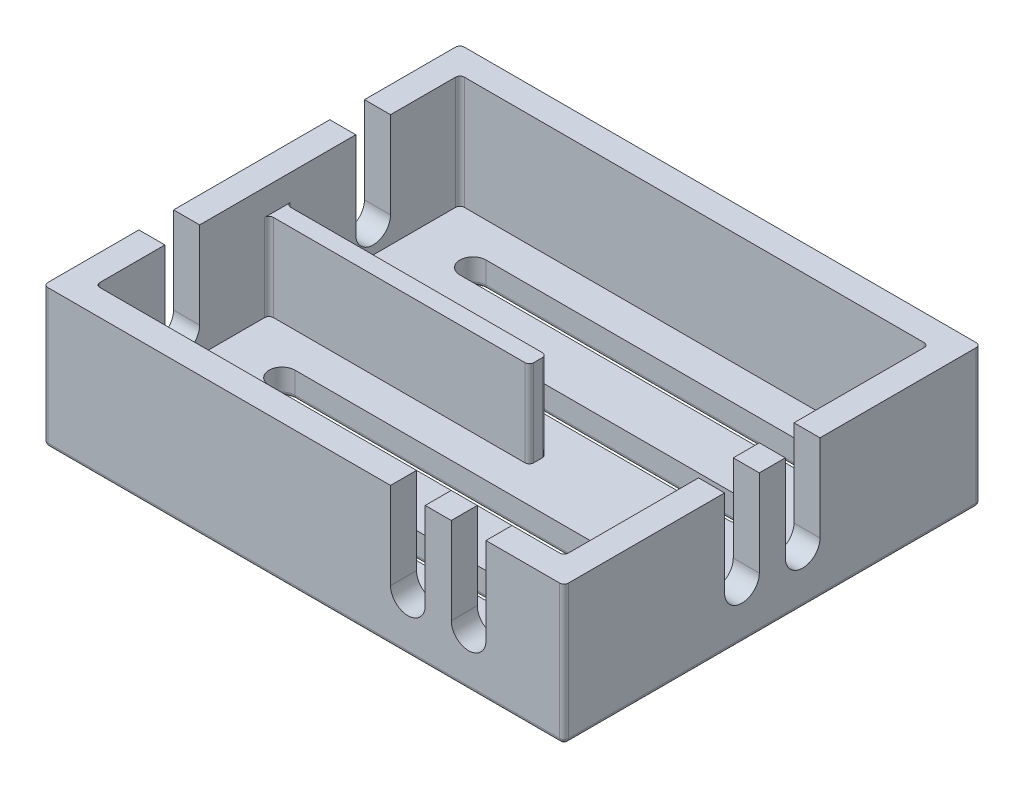
SolidWorks part; units mm, degrees
ref_plane "Front Plane" through (0, 0, 0) normal (0, 0, 1) x (1, 0, 0)
ref_plane "Top Plane" through (0, 0, 0) normal (0, 1, 0) x (1, 0, 0)
ref_plane "Right Plane" through (0, 0, 0) normal (1, 0, 0) x (0, 0, -1)
sketch "Sketch1" plane through (0, 0, 0) normal (0, 1, 0) x (1, 0, 0)
  line L1 (30, -24) -> (-30, -24)
  line L2 (30, -24) -> (30, 24)
  line L3 (30, 24) -> (-30, 24)
  line L4 (-30, -24) -> (-30, 24)
  line L5 (30, -24) -> (-30, 24) construction
  line L6 (30, 24) -> (-30, -24) construction
  point P0 (0, 0)
  dimension "D1" = 48
  dimension "D2" = 60
extrude "Boss-Extrude1" add sketch "Sketch1" along normal blind 13
sketch "Sketch2" plane through (0, 0, 0) normal (0, -1, 0) x (1, 0, 0)
  line L1 (30, -24) -> (-30, -24)
  line L2 (30, -24) -> (30, 24)
  line L3 (30, 24) -> (-30, 24)
  line L4 (-30, -24) -> (-30, 24)
  line L5 (30, -24) -> (-30, 24) construction
  line L6 (30, 24) -> (-30, -24) construction
  point P0 (0, 0)
extrude "Boss-Extrude2" add sketch "Sketch2" along normal blind 3
sketch "Sketch3" plane through (0, 13, 0) normal (0, 1, 0) x (1, 0, 0)
  line L0 (-30, 24) -> (-30, -24) construction
  line L1 (27, -21) -> (-27, -21)
  line L2 (27, -21) -> (27, 21)
  line L3 (27, 21) -> (-27, 21)
  line L4 (-27, -21) -> (-27, 21)
  line L5 (27, -21) -> (-27, 21) construction
  line L6 (27, 21) -> (-27, -21) construction
  line L7 (30, 24) -> (-30, 24) construction
  point P0 (0, 0)
  dimension "D1" = 3
  dimension "D2" = 3
extrude "Cut-Extrude1" cut sketch "Sketch3" against normal blind 13
sketch "Sketch4" plane through (27, 0, 39) normal (-1, 0, 0) x (0, 0, 1)
  line L0 (-18, 13) -> (-60, 13) construction
  line L1 (-39, 0) -> (-39, 13) construction
  line L3 (-37.5, 3) -> (-37.5, 13)
  line L4 (-37.5, 13) -> (-33.5, 13)
  line L5 (-33.5, 13) -> (-33.5, 3)
  line L6 (-40.5, 3) -> (-40.5, 13)
  line L7 (-40.5, 13) -> (-44.5, 13)
  line L8 (-44.5, 13) -> (-44.5, 3)
  line L9 (-18, 0) -> (-60, 0) construction
  arc A0 (-37.5, 3) -> (-33.5, 3) centre (-35.5, 3) ccw
  arc A1 (-40.5, 3) -> (-44.5, 3) centre (-42.5, 3) cw
  dimension "D1" = 4
  dimension "D2" = 3
  dimension "D3" = 4
  dimension "D4" = 3
extrude "Cut-Extrude2" cut sketch "Sketch4" against normal blind 3
sketch "Sketch5" plane through (0, 0, 0) normal (0, 1, 0) x (1, 0, 0)
  line L0 (-27, 21) -> (-27, -21) construction
  line L1 (3, -1) -> (-27, -1)
  line L2 (3, -1) -> (3, 1)
  line L3 (3, 1) -> (-27, 1)
  line L4 (-27, -1) -> (-27, 1)
  line L5 (3, -1) -> (-27, 1) construction
  line L6 (3, 1) -> (-27, -1) construction
  point P0 (-12, 0)
  point P8 (-27, 0)
  point P9 (-27, 0)
  dimension "D1" = 2
  dimension "D2" = 30
extrude "Boss-Extrude3" add sketch "Sketch5" along normal blind 10
sketch "Sketch6" plane through (-27, 0, 0) normal (1, 0, 0) x (0, 0, -1)
  line L0 (-13, 3) -> (-13, 13)
  line L1 (21, 13) -> (-21, 13) construction
  line L2 (-13, 13) -> (-9, 13)
  line L3 (-9, 13) -> (-9, 3)
  line L4 (-1, 0) -> (-21, 0) construction
  arc A0 (-13, 3) -> (-9, 3) centre (-11, 3) ccw
  point P12 (-11, 0)
  dimension "D1" = 4
  dimension "D2" = 3
extrude "Cut-Extrude3" cut sketch "Sketch6" against normal through all
mirror "Mirror1" about plane through (0, 0, 0) normal (0, 0, 1) of "Cut-Extrude3"
sketch "Sketch7" plane through (0, 0, 21) normal (0, 0, -1) x (-1, 0, 0)
  line L0 (-15.5, 0) -> (-15.5, 13) construction
  line L1 (-14, 3) -> (-14, 13)
  line L2 (-14, 13) -> (-10, 13)
  line L3 (-10, 13) -> (-10, 3)
  line L4 (-17, 3) -> (-17, 13)
  line L5 (-17, 13) -> (-21, 13)
  line L6 (-21, 13) -> (-21, 3)
  line L7 (27, 13) -> (-27, 13) construction
  line L8 (27, 0) -> (-27, 0) construction
  line L9 (-27, 0) -> (-27, 13) construction
  arc A0 (-14, 3) -> (-10, 3) centre (-12, 3) ccw
  arc A1 (-17, 3) -> (-21, 3) centre (-19, 3) cw
  dimension "D1" = 4
  dimension "D2" = 4
  dimension "D3" = 3
  dimension "D4" = 6
  dimension "D5" = 3
extrude "Cut-Extrude4" cut sketch "Sketch7" against normal blind 10
sketch "Sketch11" plane through (0, 0, 0) normal (0, 1, 0) x (1, 0, 0)
  line L0 (-27, 11) -> (27, 11) construction
  line L1 (-27, 21) -> (-27, 1) construction
  line L2 (27, -21) -> (27, 21) construction
  line L3 (-27, 17) -> (27, 17) construction
  line L4 (-27, 21) -> (-27, 13) construction
  line L5 (-27, 0) -> (27, 0) construction
  line L6 (-27, 9) -> (-27, -9) construction
  line L7 (0, 21) -> (0, -21) construction
  line L8 (27, 21) -> (-27, 21) construction
  line L9 (-27, -21) -> (27, -21) construction
  line L10 (-20, 5) -> (20, 5)
  line L11 (-20, 14) -> (20, 14)
  line L13 (-20, 17) -> (20, 17)
  line L14 (-20, 8) -> (20, 8)
  line L15 (0, 1) -> (0, 43) construction
  line L17 (-20, -5) -> (20, -5)
  line L18 (-20, -8) -> (20, -8)
  line L19 (-20, -17) -> (20, -17)
  line L20 (-20, -14) -> (20, -14)
  arc A0 (20, 14) -> (20, 17) centre (20, 15.5) ccw
  arc A1 (-20, 17) -> (-20, 14) centre (-20, 15.5) ccw
  arc A2 (-20, 5) -> (-20, 8) centre (-20, 6.5) cw
  arc A3 (20, 8) -> (20, 5) centre (20, 6.5) cw
  arc A4 (20, -8) -> (20, -5) centre (20, -6.5) ccw
  arc A5 (-20, -5) -> (-20, -8) centre (-20, -6.5) ccw
  arc A6 (-20, -17) -> (-20, -14) centre (-20, -15.5) cw
  arc A7 (20, -14) -> (20, -17) centre (20, -15.5) cw
  point P20 (0, 17)
  point P42 (16.612, 2.5)
  point P54 (0, -17)
  dimension "D1" = 40
  dimension "D2" = 3
  dimension "D3" = 6
extrude "Cut-Extrude5" cut sketch "Sketch11" against normal blind 10
fillet "Fillet1" radius 0.5 32 edges at (30, 5, -24) (30, 5, 24) (27, 6.5, 21) (27, 6.5, -21) (-27, 6.5, -21) (-27, 5, 1) (-27, 5, -1) (-27, 6.5, 21) (3, 5, 1) (3, 5, -1) (-30, 5, -24) (-30, 5, 24) (0, -3, 24) (30, -3, 0) (0, -3, -24) (-30, -3, 0) (0, -3, 14) (21.5, -3, 15.5) (0, -3, 17) (-21.5, -3, 15.5) (0, -3, -8) (21.5, -3, -6.5) (0, -3, -5) (-21.5, -3, -6.5) (0, -3, 5) (21.5, -3, 6.5) (0, -3, 8) (-21.5, -3, 6.5) (0, -3, -14) (-21.5, -3, -15.5) (0, -3, -17) (21.5, -3, -15.5)
